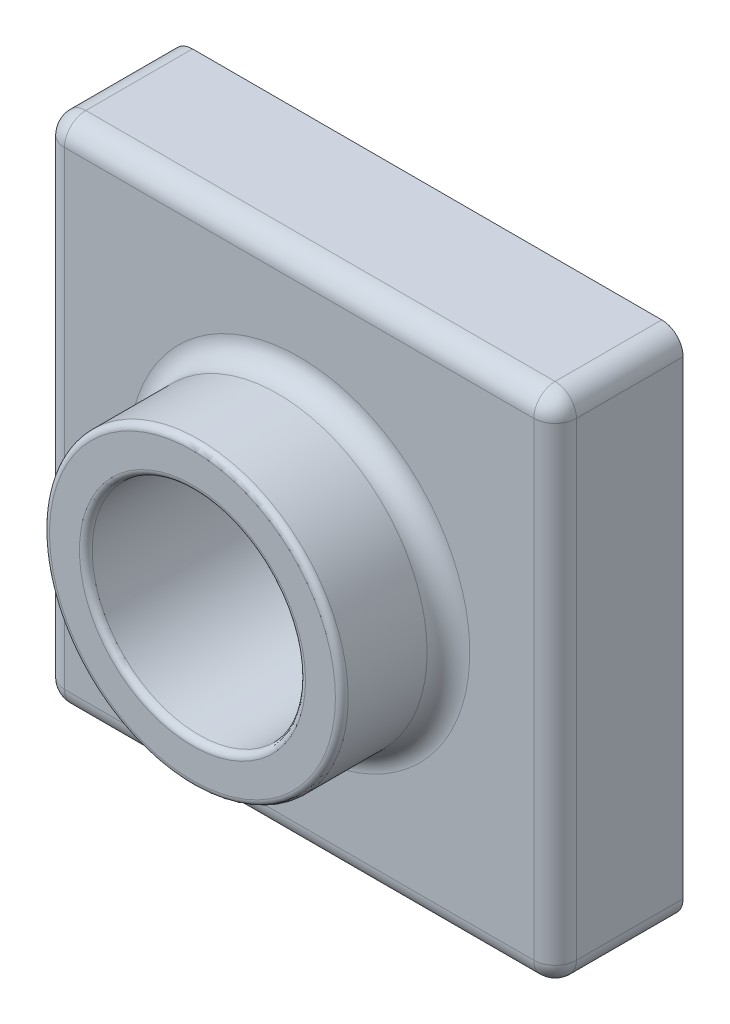
SolidWorks part; units mm, degrees
material "Acier inoxydable chromé"
ref_plane "Plan de face" through (0, 0, 0) normal (0, 0, 1) x (1, 0, 0)
ref_plane "Plan de dessus" through (0, 0, 0) normal (0, 1, 0) x (1, 0, 0)
ref_plane "Plan de droite" through (0, 0, 0) normal (1, 0, 0) x (0, 0, -1)
sketch "Esquisse2" plane through (0, 0, 0) normal (0, 0, 1) x (1, 0, 0)
  line L1 (0, 0) -> (120, 0)
  line L2 (0, 0) -> (0, 120)
  line L3 (0, 120) -> (120, 120)
  line L4 (120, 0) -> (120, 120)
  dimension "D1" = 120
  dimension "D2" = 120
extrude "Boss.-Extru.1" add sketch "Esquisse2" along normal blind 30
sketch "Esquisse3" plane through (0, 0, 30) normal (0, 0, 1) x (1, 0, 0)
  line L0 (0, 0) -> (120, 0) construction
  line L1 (0, 120) -> (0, 0) construction
  circle A0 centre (60, 60) radius 35
  point P0 (60, 60)
  dimension "D3" = 70
  dimension "D1" = 60
  dimension "D2" = 60
extrude "Boss.-Extru.3" add sketch "Esquisse3" along normal blind 25
sketch "Esquisse9" plane through (0, 0, 55) normal (0, 0, 1) x (1, 0, 0)
  circle A2 centre (60, 60) radius 25
  circle A3 centre (60, 60) radius 25
  dimension "D2" = 50
  dimension "D1" = 10
extrude "Enlèv. mat.-Extru.1" cut sketch "Esquisse9" against normal through all
fillet "Congé1" radius 5 9 edges at (0, 0, 15) (0, 120, 15) (0, 60, 30) (60, 0, 30) (120, 0, 15) (120, 60, 30) (60, 120, 30) (120, 120, 15) (95, 60, 30)
fillet "Congé2" radius 1.5 2 edges at (85, 60, 55) (95, 60, 55)
shell "Coque1" thickness 2
